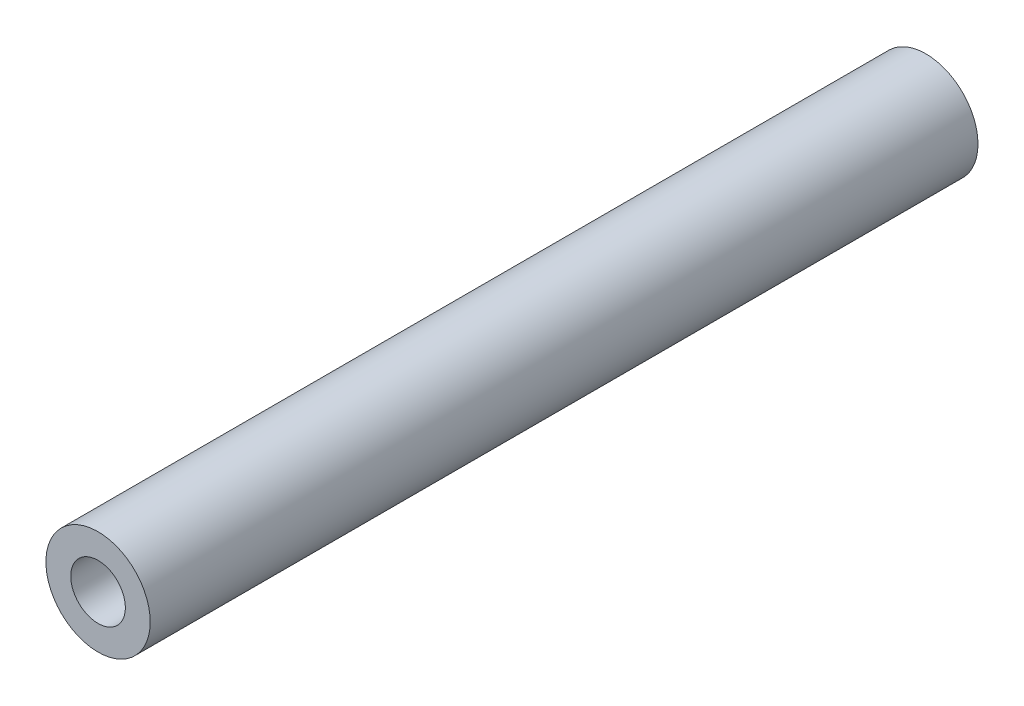
SolidWorks part; units mm, degrees
ref_plane "Front Plane" through (0, 0, 0) normal (0, 0, 1) x (1, 0, 0)
ref_plane "Top Plane" through (0, 0, 0) normal (0, 1, 0) x (1, 0, 0)
ref_plane "Right Plane" through (0, 0, 0) normal (1, 0, 0) x (0, 0, -1)
sketch "Sketch1" plane through (0, 0, 0) normal (0, 0, 1) x (1, 0, 0)
  circle A0 centre (0, 0) radius 1.65
  circle A1 centre (0, 0) radius 3.15
  dimension "D1" = 3.3
  dimension "D2" = 1.5
extrude "Boss-Extrude1" add sketch "Sketch1" along normal blind 50
